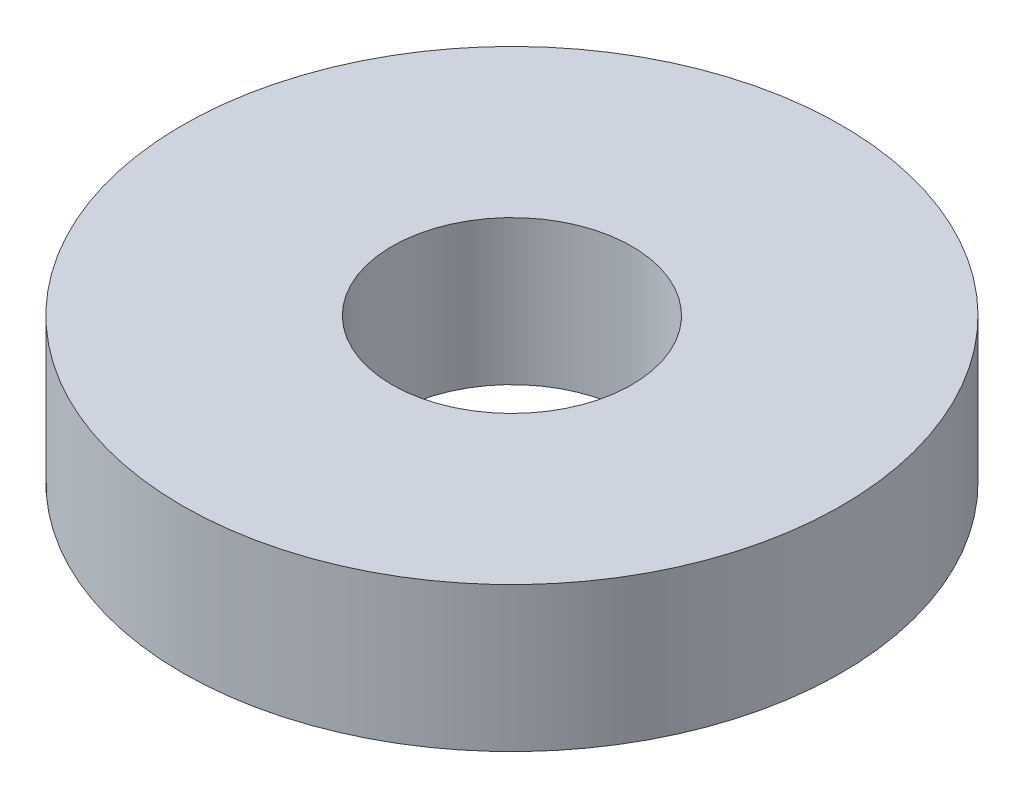
SolidWorks part; units mm, degrees
ref_plane "Front Plane" through (0, 0, 0) normal (0, 0, 1) x (1, 0, 0)
ref_plane "Top Plane" through (0, 0, 0) normal (0, 1, 0) x (1, 0, 0)
ref_plane "Right Plane" through (0, 0, 0) normal (1, 0, 0) x (0, 0, -1)
sketch "Sketch1" plane through (0, 0, 0) normal (0, 1, 0) x (1, 0, 0)
  circle A0 centre (0, 0) radius 22.7849
  circle A1 centre (0, 0) radius 8.2921
extrude "Boss-Extrude1" add sketch "Sketch1" along normal blind 10
